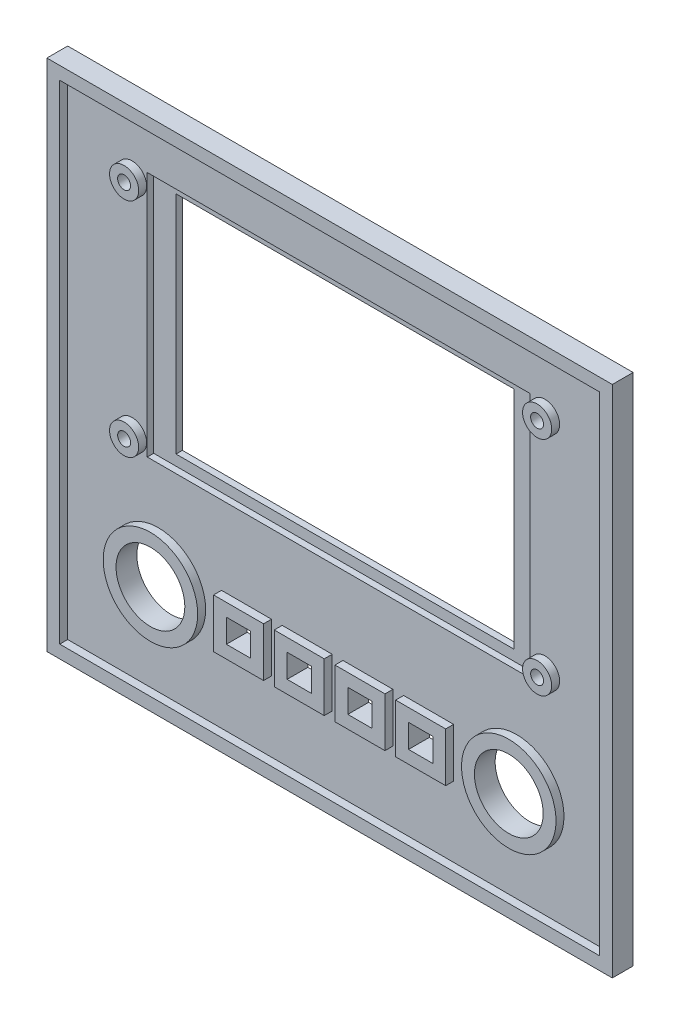
SolidWorks part; units mm, degrees
ref_plane "Front Plane" through (0, 0, 0) normal (0, 0, 1) x (1, 0, 0)
ref_plane "Top Plane" through (0, 0, 0) normal (0, 1, 0) x (1, 0, 0)
ref_plane "Right Plane" through (0, 0, 0) normal (1, 0, 0) x (0, 0, -1)
sketch "Sketch1" plane through (0, 0, 0) normal (0, 0, 1) x (1, 0, 0)
  line L0 (-10.7655, -52.97) -> (-10.7655, -58.77)
  line L1 (-41.76, -27.84) -> (41.76, -27.84)
  line L2 (-41.76, -27.84) -> (-41.76, 27.84)
  line L3 (-41.76, 27.84) -> (41.76, 27.84)
  line L4 (41.76, -27.84) -> (41.76, 27.84)
  line L5 (-41.76, -27.84) -> (41.76, 27.84) construction
  line L6 (-41.76, 27.84) -> (41.76, -27.84) construction
  line L7 (-70.1155, 44.4994) -> (69.5845, 44.4994)
  line L8 (-70.1155, 44.4994) -> (-70.1155, -82.5006)
  line L9 (-70.1155, -82.5006) -> (69.5845, -82.5006)
  line L10 (69.5845, 44.4994) -> (69.5845, -82.5006)
  line L11 (-25.7655, -52.97) -> (-19.7655, -52.97)
  line L12 (-25.7655, -52.97) -> (-25.7655, -58.77)
  line L13 (-25.7655, -58.77) -> (-19.7655, -58.77)
  line L14 (-19.7655, -52.97) -> (-19.7655, -58.77)
  line L15 (44.0042, -55.87) -> (-44.5351, -55.87) construction
  line L16 (-10.7655, -52.97) -> (-4.7655, -52.97)
  line L17 (-4.7655, -52.97) -> (-4.7655, -58.77)
  line L18 (-10.7655, -58.77) -> (-4.7655, -58.77)
  line L19 (4.2345, -52.97) -> (4.2345, -58.77)
  line L20 (4.2345, -52.97) -> (10.2345, -52.97)
  line L21 (10.2345, -52.97) -> (10.2345, -58.77)
  line L22 (4.2345, -58.77) -> (10.2345, -58.77)
  line L23 (19.2345, -52.97) -> (19.2345, -58.77)
  line L24 (19.2345, -52.97) -> (25.2345, -52.97)
  line L25 (25.2345, -52.97) -> (25.2345, -58.77)
  line L26 (19.2345, -58.77) -> (25.2345, -58.77)
  line L27 (-4.7655, -55.87) -> (4.2345, -55.87) construction
  line L29 (-4.7655, -55.87) -> (4.2345, -55.87) construction
  line L30 (-70.1155, -19.0006) -> (-58.5356, -19.0006) construction
  line L31 (58.0047, -19.0006) -> (69.5845, -19.0006) construction
  line L32 (-0.2655, -82.5006) -> (-0.2655, -69.8704) construction
  line L33 (-0.2655, 44.4994) -> (-0.2655, 31.8693) construction
  line L34 (-58.5356, 31.8693) -> (-58.5356, -69.8704)
  line L35 (58.0047, 31.8693) -> (-58.5356, 31.8693)
  line L36 (58.0047, -69.8704) -> (58.0047, 31.8693)
  line L37 (-58.5356, -69.8704) -> (58.0047, -69.8704)
  line L38 (-58.5356, 31.8693) -> (-58.5356, -69.8704)
  line L39 (58.0047, 31.8693) -> (-58.5356, 31.8693)
  line L40 (58.0047, -69.8704) -> (58.0047, 31.8693)
  line L41 (-58.5356, -69.8704) -> (58.0047, -69.8704)
  circle A0 centre (44.0042, -55.87) radius 8.5
  circle A1 centre (-44.5351, -55.87) radius 8.5
  point P0 (0, 0)
  point P16 (-25.7655, -55.87)
  dimension "D12" = 17
  dimension "D13" = 17
  dimension "D1" = 55.68
  dimension "D2" = 83.52
  dimension "D3" = 139.7
  dimension "D4" = 127
  dimension "D5" = 0
  dimension "D6" = 14.0005
  dimension "D7" = 14.0005
  dimension "D8" = 14.0005
  dimension "D9" = 14.0005
  dimension "D14" = 6
  dimension "D15" = 5.8
  dimension "D16" = 4
extrude "Boss-Extrude1" add sketch "Sketch1" along normal blind 5.1375
sketch "Sketch2" plane through (0, 0, 5.1375) normal (0, 0, 1) x (1, 0, 0)
  line L0 (41.76, -27.84) -> (41.76, 27.84) construction
  line L1 (-41.76, -27.84) -> (41.76, -27.84) construction
  line L2 (-41.76, -27.84) -> (-41.76, 27.84) construction
  line L3 (-41.76, 27.84) -> (41.76, 27.84) construction
  line L4 (41.76, -27.84) -> (41.76, 27.84)
  line L5 (-41.76, -27.84) -> (41.76, -27.84)
  line L6 (-41.76, -27.84) -> (-41.76, 27.84)
  line L7 (-41.76, 27.84) -> (41.76, 27.84)
  line L9 (47.285, 30.44) -> (-47.285, 30.44)
  line L10 (47.285, 30.44) -> (47.285, -30.44)
  line L11 (47.285, -30.44) -> (-47.285, -30.44)
  line L12 (-47.285, 30.44) -> (-47.285, -30.44)
  line L13 (47.285, 30.44) -> (-47.285, -30.44) construction
  line L14 (47.285, -30.44) -> (-47.285, 30.44) construction
  point P3 (0, 0)
  dimension "D1" = 94.57
  dimension "D2" = 60.88
extrude "Cut-Extrude1" cut sketch "Sketch2" against normal blind 3.55
sketch "Sketch3" plane through (0, 0, 5.1375) normal (0, 0, 1) x (1, 0, 0)
  circle A0 centre (51.005, -27.4503) radius 1.6 construction
  circle A1 centre (-51.035, 27.4497) radius 1.6 construction
  circle A2 centre (51.005, 27.4497) radius 1.6 construction
  circle A3 centre (51.005, -27.4503) radius 1.6
  circle A4 centre (-51.035, 27.4497) radius 1.6
  circle A5 centre (51.005, 27.4497) radius 1.6
  circle A6 centre (-51.035, -27.4499) radius 1.6002 construction
  circle A7 centre (-51.035, -27.4499) radius 1.6002
extrude "Cut-Extrude2" cut sketch "Sketch3" against normal blind 10
sketch "Sketch4" plane through (0, 0, 5.1375) normal (0, 0, 1) x (1, 0, 0)
  line L8 (66.4095, -79.3256) -> (66.4095, 41.3244)
  line L9 (66.4095, 41.3244) -> (-66.9405, 41.3244)
  line L10 (-66.9405, 41.3244) -> (-66.9405, -79.3256)
  line L11 (-66.9405, -79.3256) -> (66.4095, -79.3256)
  line L12 (66.4095, -79.3256) -> (66.4095, 41.3244)
  line L13 (66.4095, 41.3244) -> (-66.9405, 41.3244)
  line L14 (-66.9405, 41.3244) -> (-66.9405, -79.3256)
  line L15 (-66.9405, -79.3256) -> (66.4095, -79.3256)
  line L16 (-1.5905, -61.945) -> (-1.5905, -49.795)
  line L17 (-1.5905, -49.795) -> (-13.9405, -49.795)
  line L21 (-28.9405, -49.795) -> (-28.9405, -61.945)
  line L22 (13.4095, -49.795) -> (1.0595, -49.795)
  line L23 (13.4095, -61.945) -> (13.4095, -49.795)
  line L24 (1.0595, -61.945) -> (13.4095, -61.945)
  line L25 (1.0595, -49.795) -> (1.0595, -61.945)
  line L26 (13.4095, -49.795) -> (1.0595, -49.795)
  line L27 (13.4095, -61.945) -> (13.4095, -49.795)
  line L28 (1.0595, -61.945) -> (13.4095, -61.945)
  line L29 (1.0595, -49.795) -> (1.0595, -61.945)
  line L30 (-16.5905, -49.795) -> (-28.9405, -49.795)
  line L31 (-16.5905, -61.945) -> (-16.5905, -49.795)
  line L32 (-28.9405, -61.945) -> (-16.5905, -61.945)
  line L33 (-28.9405, -49.795) -> (-28.9405, -61.945)
  line L34 (-16.5905, -49.795) -> (-28.9405, -49.795)
  line L35 (-16.5905, -61.945) -> (-16.5905, -49.795)
  line L36 (-28.9405, -61.945) -> (-16.5905, -61.945)
  line L39 (-13.9405, -49.795) -> (-13.9405, -61.945)
  line L40 (-13.9405, -61.945) -> (-1.5905, -61.945)
  line L41 (-1.5905, -61.945) -> (-1.5905, -49.795)
  line L42 (-1.5905, -49.795) -> (-13.9405, -49.795)
  line L43 (-13.9405, -49.795) -> (-13.9405, -61.945)
  line L44 (-13.9405, -61.945) -> (-1.5905, -61.945)
  line L280 (16.0595, -61.945) -> (28.4095, -61.945)
  line L281 (28.4095, -61.945) -> (28.4095, -49.795)
  line L282 (28.4095, -49.795) -> (16.0595, -49.795)
  line L283 (16.0595, -49.795) -> (16.0595, -61.945)
  line L284 (16.0595, -61.945) -> (28.4095, -61.945)
  line L285 (28.4095, -61.945) -> (28.4095, -49.795)
  line L286 (28.4095, -49.795) -> (16.0595, -49.795)
  line L287 (16.0595, -49.795) -> (16.0595, -61.945)
  circle A2 centre (44.0042, -55.87) radius 11.675
  circle A3 centre (44.0042, -55.87) radius 11.675
  circle A103 centre (-44.5351, -55.87) radius 11.675
  circle A104 centre (-44.5351, -55.87) radius 11.675
  circle A106 centre (-51.035, -27.4499) radius 3.6002
  circle A107 centre (-51.035, -27.4499) radius 3.6002
  circle A109 centre (-51.035, 27.4497) radius 3.6
  circle A110 centre (-51.035, 27.4497) radius 3.6
  circle A116 centre (51.005, 27.4497) radius 3.6
  circle A117 centre (51.005, 27.4497) radius 3.6
  circle A119 centre (51.005, -27.4503) radius 3.6
  circle A120 centre (51.005, -27.4503) radius 3.6
  line M31 (-47.285, -30.44) -> (-47.285, 30.44)
  line M32 (-47.285, 30.44) -> (47.285, 30.44)
  line M33 (47.285, 30.44) -> (47.285, -30.44)
  line M34 (47.285, -30.44) -> (-47.285, -30.44)
  dimension "D1" = 3.175
  dimension "D2" = 3.175
  dimension "D3" = 2
  dimension "D4" = 2
  dimension "D5" = 2
  dimension "D6" = 2
  dimension "D7" = 3.175
  dimension "D8" = 3.175
  dimension "D9" = 3.175
  dimension "D10" = 3.175
  dimension "D11" = 3.175
extrude "Cut-Extrude3" cut sketch "Sketch4" against normal blind 1.9625 contours L14 L15 L12 L13 A120 A107 A110 A117 A104 A3 L287 L286 L285 L284 L44 L43 L42 L41 L36 L33 L34 L35 L29 L26 L27 L28 M34 M31 M32 M33
equation "\"depth\"= 3.55 + 1.5875"
equation "\"D1@Boss-Extrude1\"=\"depth\""
equation "\"inset\"= \"depth\" - 1.5875"
equation "\"D1@Cut-Extrude1\"=\"inset\""
equation "\"shell\"= \"depth\" - 3.175"
equation "\"D1@Cut-Extrude3\"=\"shell\""
